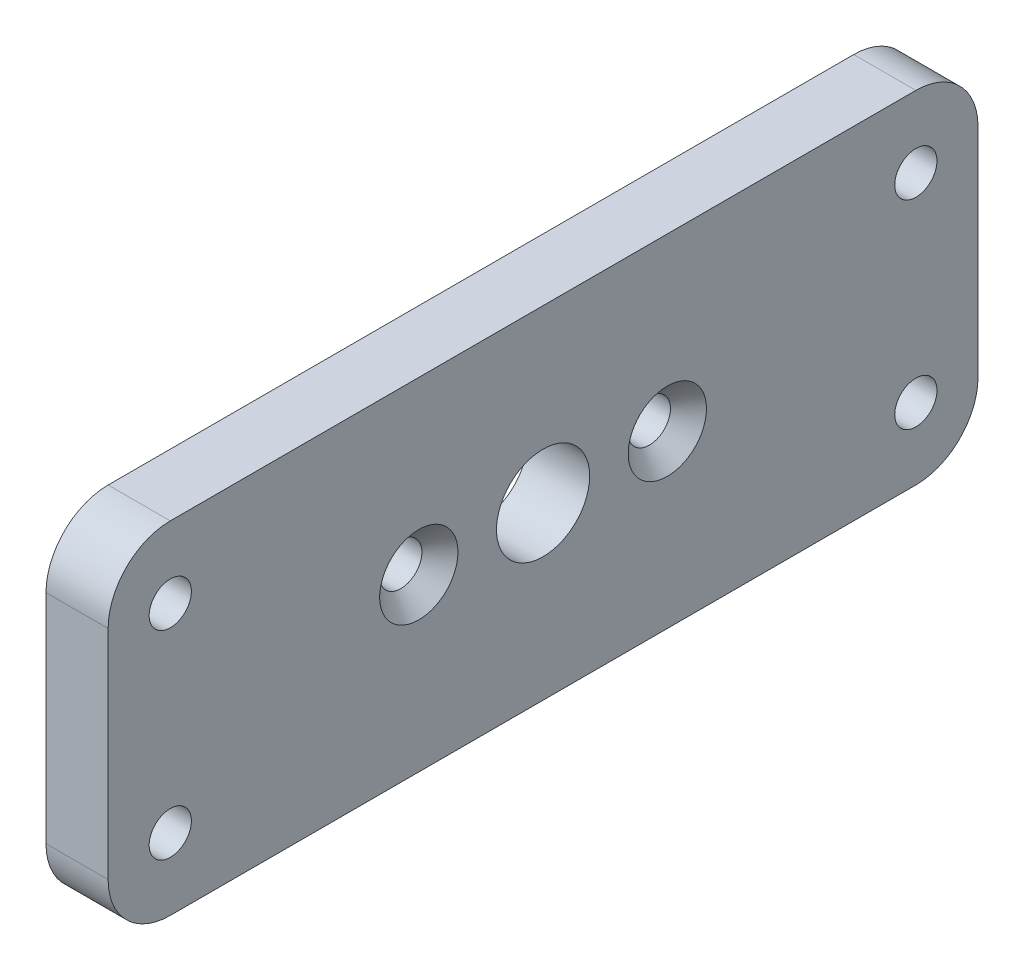
SolidWorks part; units mm, degrees
ref_plane "Front Plane" through (0, 0, 0) normal (0, 0, 1) x (1, 0, 0)
ref_plane "Top Plane" through (0, 0, 0) normal (0, 1, 0) x (1, 0, 0)
ref_plane "Right Plane" through (0, 0, 0) normal (1, 0, 0) x (0, 0, -1)
sketch "Sketch1" plane through (0, 0, 0) normal (1, 0, 0) x (0, 0, -1)
  line L0 (-30, -13.75) -> (30, -13.75)
  line L1 (-35, -8.75) -> (-35, 8.75)
  line L2 (35, -8.75) -> (35, 8.75)
  line L3 (-30, 13.75) -> (30, 13.75)
  line L4 (-35, -13.75) -> (35, 13.75) construction
  line L5 (35, -13.75) -> (-35, 13.75) construction
  arc A0 (-35, 8.75) -> (-30, 13.75) centre (-30, 8.75) cw
  arc A1 (-35, -8.75) -> (-30, -13.75) centre (-30, -8.75) ccw
  arc A2 (30, -13.75) -> (35, -8.75) centre (30, -8.75) ccw
  arc A3 (35, 8.75) -> (30, 13.75) centre (30, 8.75) ccw
  circle A4 centre (0, 0) radius 3.75
  point P1 (0, 0)
  dimension "D3" = 5
  dimension "D4" = 7.5
  dimension "D1" = 27.5
  dimension "D2" = 70
extrude "Boss-Extrude1" add sketch "Sketch1" along normal blind 5
sketch "Sketch2" plane through (5, 0, 0) normal (1, 0, 0) x (0, 0, -1)
  line L0 (-35, 0) -> (35, 0) construction
  line L1 (-35, 8.75) -> (-35, -8.75) construction
  line L2 (35, -8.75) -> (35, 8.75) construction
  line L3 (-30, 13.75) -> (-30, -13.75) construction
  line L4 (30, 13.75) -> (-30, 13.75) construction
  line L5 (-30, -13.75) -> (30, -13.75) construction
  line L6 (30, 13.75) -> (30, -13.75) construction
  point P6 (10, 0)
  point P7 (-10, 0)
  point P8 (-30, 0)
  point P10 (30, 0)
  point P19 (-30, 8)
  point P20 (30, 8)
  point P21 (30, -8)
  point P22 (-30, -8)
  point P23 (0, 0)
  point P24 (0, 0)
  dimension "D1" = 10
  dimension "D2" = 10
  dimension "D3" = 20
  dimension "D4" = 20
  dimension "D5" = 8
  dimension "D6" = 8
hole_wizard "CSK for M3 Countersunk Flat Head Screw1" positions "3DSketch3" profile "Sketch5" countersink size "M3" standard "ISO" end condition through all
sketch3d "3DSketch3"
  point P0 (5, 0, 10)
  point P3 (5, 0, -10)
sketch "Sketch5" plane through (5, 0, 10) normal (0, 1, 0) x (0, 0, -1)
  line L0 (0, 0) -> (0, 5)
  line L1 (0, 5) -> (1.7, 5)
  line L2 (1.7, 5) -> (1.7, 1.45)
  line L3 (1.7, 1.45) -> (3.15, 0)
  line L5 (3.15, 0) -> (0, 0)
  line L6 (-1.7, 1.45) -> (-3.15, 0) construction
  line L11 (0, -6.35) -> (0, 107.95) construction
  dimension "Thru Hole Dia." = 3.4
  dimension "Thru Hole Depth" = 5
  dimension "Near C'Sink Dia." = 6.3
  dimension "Near C'Sink Angle" = 90
sketch "Sketch7" plane through (0, 0, 0) normal (-1, 0, 0) x (0, 0, 1)
  point P0 (-30, 8)
  point P1 (-30, -8)
  point P3 (30, -8)
  point P5 (30, 8)
hole_wizard "M3 Clearance Hole3" positions "3DSketch5" profile "Sketch8" hole size "M3" standard "ISO"
sketch3d "3DSketch5"
  point P0 (0, 8, 30)
  point P2 (0, -8, 30)
  point P4 (0, -8, -30)
  point P6 (0, 8, -30)
  point P9 (0, 0, 0)
  point P13 (0, 0, 0)
  point P14 (0, 0, 0)
  point P16 (0, 0, 0)
  point P19 (0, 0, 0)
sketch "Sketch8" plane through (0, 8, 30) normal (0, 1, 0) x (0, 0, 1)
  line L0 (0, 0) -> (0, 6.0215)
  line L1 (0, 6.0215) -> (1.7, 5)
  line L2 (1.7, 5) -> (1.7, 0)
  line L5 (1.7, 0) -> (0, 0)
  line L10 (0, 6.0215) -> (-1.7, 5) construction
  line L11 (0, -6.35) -> (0, 107.95) construction
  dimension "Hole Dia." = 3.4
  dimension "Hole Depth" = 5
  dimension "Drill Angle" = 118
